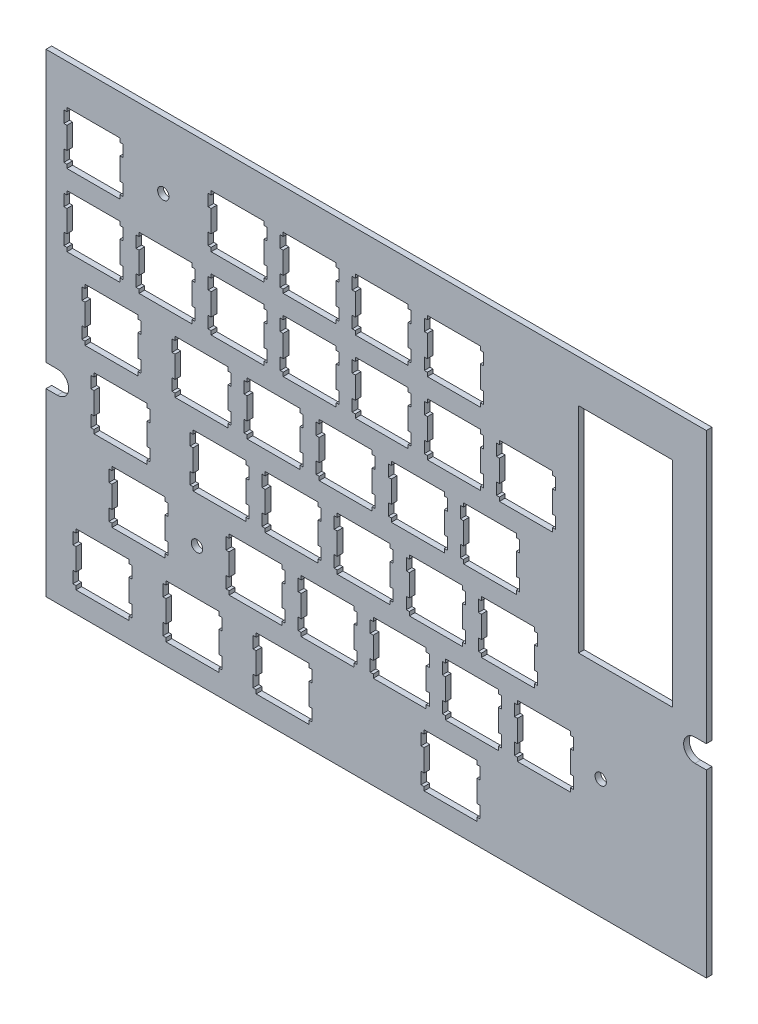
SolidWorks part; units mm, degrees
ref_plane "前视基准面" through (0, 0, 0) normal (0, 0, 1) x (1, 0, 0)
ref_plane "上视基准面" through (0, 0, 0) normal (0, 1, 0) x (1, 0, 0)
ref_plane "右视基准面" through (0, 0, 0) normal (1, 0, 0) x (0, 0, -1)
sketch "Model" plane through (0, 0, 0) normal (0, 0, 1) x (1, 0, 0)
  line L0 (392.6286, 110.8829) -> (392.6286, 109.8825)
  line L1 (392.6286, 109.8825) -> (391.8278, 109.8825)
  line L2 (391.8278, 109.8825) -> (391.8278, 106.7832)
  line L3 (391.8278, 106.7832) -> (392.6286, 106.7832)
  line L4 (392.6286, 106.7832) -> (392.6286, 100.9816)
  line L5 (392.6286, 100.9816) -> (391.8278, 100.9816)
  line L6 (391.8278, 100.9816) -> (391.8278, 97.8825)
  line L7 (391.8278, 97.8825) -> (392.6286, 97.8825)
  line L8 (392.6286, 97.8825) -> (392.6286, 96.882)
  line L9 (392.6286, 96.882) -> (406.6279, 96.882)
  line L10 (406.6279, 96.882) -> (406.6279, 97.8825)
  line L11 (406.6279, 97.8825) -> (407.4287, 97.8825)
  line L12 (407.4287, 97.8825) -> (407.4287, 100.9816)
  line L13 (407.4287, 100.9816) -> (406.6279, 100.9816)
  line L14 (406.6279, 100.9816) -> (406.6279, 106.7832)
  line L15 (406.6279, 106.7832) -> (407.4287, 106.7832)
  line L16 (407.4287, 106.7832) -> (407.4287, 109.8825)
  line L17 (407.4287, 109.8825) -> (406.6279, 109.8825)
  line L18 (406.6279, 109.8825) -> (406.6279, 110.8829)
  line L19 (406.6279, 110.8829) -> (392.6286, 110.8829)
  line L20 (368.8146, 110.8829) -> (368.8146, 109.8825)
  line L21 (368.8146, 109.8825) -> (368.0154, 109.8825)
  line L22 (368.0154, 109.8825) -> (368.0154, 106.7832)
  line L23 (368.0154, 106.7832) -> (368.8146, 106.7832)
  line L24 (368.8146, 106.7832) -> (368.8146, 100.9816)
  line L25 (368.8146, 100.9816) -> (368.0154, 100.9816)
  line L26 (368.0154, 100.9816) -> (368.0154, 97.8825)
  line L27 (368.0154, 97.8825) -> (368.8146, 97.8825)
  line L28 (368.8146, 97.8825) -> (368.8146, 96.882)
  line L29 (368.8146, 96.882) -> (382.8154, 96.882)
  line L30 (382.8154, 96.882) -> (382.8154, 97.8825)
  line L31 (382.8154, 97.8825) -> (383.6148, 97.8825)
  line L32 (383.6148, 97.8825) -> (383.6148, 100.9816)
  line L33 (383.6148, 100.9816) -> (382.8154, 100.9816)
  line L34 (382.8154, 100.9816) -> (382.8154, 106.7832)
  line L35 (382.8154, 106.7832) -> (383.6148, 106.7832)
  line L36 (383.6148, 106.7832) -> (383.6148, 109.8825)
  line L37 (383.6148, 109.8825) -> (382.8154, 109.8825)
  line L38 (382.8154, 109.8825) -> (382.8154, 110.8829)
  line L39 (382.8154, 110.8829) -> (368.8146, 110.8829)
  line L40 (345.0035, 110.8829) -> (345.0035, 109.8825)
  line L41 (345.0035, 109.8825) -> (344.2028, 109.8825)
  line L42 (344.2028, 109.8825) -> (344.2028, 106.7832)
  line L43 (344.2028, 106.7832) -> (345.0035, 106.7832)
  line L44 (345.0035, 106.7832) -> (345.0035, 100.9816)
  line L45 (345.0035, 100.9816) -> (344.2028, 100.9816)
  line L46 (344.2028, 100.9816) -> (344.2028, 97.8825)
  line L47 (344.2028, 97.8825) -> (345.0035, 97.8825)
  line L48 (345.0035, 97.8825) -> (345.0035, 96.882)
  line L49 (345.0035, 96.882) -> (359.003, 96.882)
  line L50 (359.003, 96.882) -> (359.003, 97.8825)
  line L51 (359.003, 97.8825) -> (359.8036, 97.8825)
  line L52 (359.8036, 97.8825) -> (359.8036, 100.9816)
  line L53 (359.8036, 100.9816) -> (359.003, 100.9816)
  line L54 (359.003, 100.9816) -> (359.003, 106.7832)
  line L55 (359.003, 106.7832) -> (359.8036, 106.7832)
  line L56 (359.8036, 106.7832) -> (359.8036, 109.8825)
  line L57 (359.8036, 109.8825) -> (359.003, 109.8825)
  line L58 (359.003, 109.8825) -> (359.003, 110.8829)
  line L59 (359.003, 110.8829) -> (345.0035, 110.8829)
  line L60 (461.6846, 129.9314) -> (461.6846, 128.9311)
  line L61 (461.6846, 128.9311) -> (460.8836, 128.9311)
  line L62 (460.8836, 128.9311) -> (460.8836, 125.8332)
  line L63 (460.8836, 125.8332) -> (461.6846, 125.8332)
  line L64 (461.6846, 125.8332) -> (461.6846, 120.0317)
  line L65 (461.6846, 120.0317) -> (460.8836, 120.0317)
  line L66 (460.8836, 120.0317) -> (460.8836, 116.9311)
  line L67 (460.8836, 116.9311) -> (461.6846, 116.9311)
  line L68 (461.6846, 116.9311) -> (461.6846, 115.932)
  line L69 (461.6846, 115.932) -> (475.6846, 115.932)
  line L70 (475.6846, 115.932) -> (475.6846, 116.9311)
  line L71 (475.6846, 116.9311) -> (476.4836, 116.9311)
  line L72 (476.4836, 116.9311) -> (476.4836, 120.0317)
  line L73 (476.4836, 120.0317) -> (475.6846, 120.0317)
  line L74 (475.6846, 120.0317) -> (475.6846, 125.8332)
  line L75 (475.6846, 125.8332) -> (476.4836, 125.8332)
  line L76 (476.4836, 125.8332) -> (476.4836, 128.9311)
  line L77 (476.4836, 128.9311) -> (475.6846, 128.9311)
  line L78 (475.6846, 128.9311) -> (475.6846, 129.9314)
  line L79 (475.6846, 129.9314) -> (461.6846, 129.9314)
  line L80 (442.6346, 129.9314) -> (442.6346, 128.9311)
  line L81 (442.6346, 128.9311) -> (441.8336, 128.9311)
  line L82 (441.8336, 128.9311) -> (441.8336, 125.8332)
  line L83 (441.8336, 125.8332) -> (442.6346, 125.8332)
  line L84 (442.6346, 125.8332) -> (442.6346, 120.0317)
  line L85 (442.6346, 120.0317) -> (441.8336, 120.0317)
  line L86 (441.8336, 120.0317) -> (441.8336, 116.9311)
  line L87 (441.8336, 116.9311) -> (442.6346, 116.9311)
  line L88 (442.6346, 116.9311) -> (442.6346, 115.932)
  line L89 (442.6346, 115.932) -> (456.6346, 115.932)
  line L90 (456.6346, 115.932) -> (456.6346, 116.9311)
  line L91 (456.6346, 116.9311) -> (457.4336, 116.9311)
  line L92 (457.4336, 116.9311) -> (457.4336, 120.0317)
  line L93 (457.4336, 120.0317) -> (456.6346, 120.0317)
  line L94 (456.6346, 120.0317) -> (456.6346, 125.8332)
  line L95 (456.6346, 125.8332) -> (457.4336, 125.8332)
  line L96 (457.4336, 125.8332) -> (457.4336, 128.9311)
  line L97 (457.4336, 128.9311) -> (456.6346, 128.9311)
  line L98 (456.6346, 128.9311) -> (456.6346, 129.9314)
  line L99 (456.6346, 129.9314) -> (442.6346, 129.9314)
  line L100 (423.5848, 129.9314) -> (423.5848, 128.9311)
  line L101 (423.5848, 128.9311) -> (422.784, 128.9311)
  line L102 (422.784, 128.9311) -> (422.784, 125.8332)
  line L103 (422.784, 125.8332) -> (423.5848, 125.8332)
  line L104 (423.5848, 125.8332) -> (423.5848, 120.0317)
  line L105 (423.5848, 120.0317) -> (422.784, 120.0317)
  line L106 (422.784, 120.0317) -> (422.784, 116.9311)
  line L107 (422.784, 116.9311) -> (423.5848, 116.9311)
  line L108 (423.5848, 116.9311) -> (423.5848, 115.932)
  line L109 (423.5848, 115.932) -> (437.5841, 115.932)
  line L110 (437.5841, 115.932) -> (437.5841, 116.9311)
  line L111 (437.5841, 116.9311) -> (438.3835, 116.9311)
  line L112 (438.3835, 116.9311) -> (438.3835, 120.0317)
  line L113 (438.3835, 120.0317) -> (437.5841, 120.0317)
  line L114 (437.5841, 120.0317) -> (437.5841, 125.8332)
  line L115 (437.5841, 125.8332) -> (438.3835, 125.8332)
  line L116 (438.3835, 125.8332) -> (438.3835, 128.9311)
  line L117 (438.3835, 128.9311) -> (437.5841, 128.9311)
  line L118 (437.5841, 128.9311) -> (437.5841, 129.9314)
  line L119 (437.5841, 129.9314) -> (423.5848, 129.9314)
  line L120 (404.5348, 129.9314) -> (404.5348, 128.9311)
  line L121 (404.5348, 128.9311) -> (403.734, 128.9311)
  line L122 (403.734, 128.9311) -> (403.734, 125.8332)
  line L123 (403.734, 125.8332) -> (404.5348, 125.8332)
  line L124 (404.5348, 125.8332) -> (404.5348, 120.0317)
  line L125 (404.5348, 120.0317) -> (403.734, 120.0317)
  line L126 (403.734, 120.0317) -> (403.734, 116.9311)
  line L127 (403.734, 116.9311) -> (404.5348, 116.9311)
  line L128 (404.5348, 116.9311) -> (404.5348, 115.932)
  line L129 (404.5348, 115.932) -> (418.5341, 115.932)
  line L130 (418.5341, 115.932) -> (418.5341, 116.9311)
  line L131 (418.5341, 116.9311) -> (419.3335, 116.9311)
  line L132 (419.3335, 116.9311) -> (419.3335, 120.0317)
  line L133 (419.3335, 120.0317) -> (418.5341, 120.0317)
  line L134 (418.5341, 120.0317) -> (418.5341, 125.8332)
  line L135 (418.5341, 125.8332) -> (419.3335, 125.8332)
  line L136 (419.3335, 125.8332) -> (419.3335, 128.9311)
  line L137 (419.3335, 128.9311) -> (418.5341, 128.9311)
  line L138 (418.5341, 128.9311) -> (418.5341, 129.9314)
  line L139 (418.5341, 129.9314) -> (404.5348, 129.9314)
  line L140 (385.4848, 129.9314) -> (385.4848, 128.9311)
  line L141 (385.4848, 128.9311) -> (384.684, 128.9311)
  line L142 (384.684, 128.9311) -> (384.684, 125.8332)
  line L143 (384.684, 125.8332) -> (385.4848, 125.8332)
  line L144 (385.4848, 125.8332) -> (385.4848, 120.0317)
  line L145 (385.4848, 120.0317) -> (384.684, 120.0317)
  line L146 (384.684, 120.0317) -> (384.684, 116.9311)
  line L147 (384.684, 116.9311) -> (385.4848, 116.9311)
  line L148 (385.4848, 116.9311) -> (385.4848, 115.932)
  line L149 (385.4848, 115.932) -> (399.4841, 115.932)
  line L150 (399.4841, 115.932) -> (399.4841, 116.9311)
  line L151 (399.4841, 116.9311) -> (400.2835, 116.9311)
  line L152 (400.2835, 116.9311) -> (400.2835, 120.0317)
  line L153 (400.2835, 120.0317) -> (399.4841, 120.0317)
  line L154 (399.4841, 120.0317) -> (399.4841, 125.8332)
  line L155 (399.4841, 125.8332) -> (400.2835, 125.8332)
  line L156 (400.2835, 125.8332) -> (400.2835, 128.9311)
  line L157 (400.2835, 128.9311) -> (399.4841, 128.9311)
  line L158 (399.4841, 128.9311) -> (399.4841, 129.9314)
  line L159 (399.4841, 129.9314) -> (385.4848, 129.9314)
  line L160 (452.1596, 148.9815) -> (452.1596, 147.981)
  line L161 (452.1596, 147.981) -> (451.3586, 147.981)
  line L162 (451.3586, 147.981) -> (451.3586, 144.8832)
  line L163 (451.3586, 144.8832) -> (452.1596, 144.8832)
  line L164 (452.1596, 144.8832) -> (452.1596, 139.0818)
  line L165 (452.1596, 139.0818) -> (451.3586, 139.0818)
  line L166 (451.3586, 139.0818) -> (451.3586, 135.9812)
  line L167 (451.3586, 135.9812) -> (452.1596, 135.9812)
  line L168 (452.1596, 135.9812) -> (452.1596, 134.9822)
  line L169 (452.1596, 134.9822) -> (466.1596, 134.9822)
  line L170 (466.1596, 134.9822) -> (466.1596, 135.9812)
  line L171 (466.1596, 135.9812) -> (466.9586, 135.9812)
  line L172 (466.9586, 135.9812) -> (466.9586, 139.0818)
  line L173 (466.9586, 139.0818) -> (466.1596, 139.0818)
  line L174 (466.1596, 139.0818) -> (466.1596, 144.8832)
  line L175 (466.1596, 144.8832) -> (466.9586, 144.8832)
  line L176 (466.9586, 144.8832) -> (466.9586, 147.981)
  line L177 (466.9586, 147.981) -> (466.1596, 147.981)
  line L178 (466.1596, 147.981) -> (466.1596, 148.9815)
  line L179 (466.1596, 148.9815) -> (452.1596, 148.9815)
  line L180 (433.1098, 148.9815) -> (433.1098, 147.981)
  line L181 (433.1098, 147.981) -> (432.309, 147.981)
  line L182 (432.309, 147.981) -> (432.309, 144.8832)
  line L183 (432.309, 144.8832) -> (433.1098, 144.8832)
  line L184 (433.1098, 144.8832) -> (433.1098, 139.0818)
  line L185 (433.1098, 139.0818) -> (432.309, 139.0818)
  line L186 (432.309, 139.0818) -> (432.309, 135.9812)
  line L187 (432.309, 135.9812) -> (433.1098, 135.9812)
  line L188 (433.1098, 135.9812) -> (433.1098, 134.9822)
  line L189 (433.1098, 134.9822) -> (447.1096, 134.9822)
  line L190 (447.1096, 134.9822) -> (447.1096, 135.9812)
  line L191 (447.1096, 135.9812) -> (447.9086, 135.9812)
  line L192 (447.9086, 135.9812) -> (447.9086, 139.0818)
  line L193 (447.9086, 139.0818) -> (447.1096, 139.0818)
  line L194 (447.1096, 139.0818) -> (447.1096, 144.8832)
  line L195 (447.1096, 144.8832) -> (447.9086, 144.8832)
  line L196 (447.9086, 144.8832) -> (447.9086, 147.981)
  line L197 (447.9086, 147.981) -> (447.1096, 147.981)
  line L198 (447.1096, 147.981) -> (447.1096, 148.9815)
  line L199 (447.1096, 148.9815) -> (433.1098, 148.9815)
  line L200 (414.0598, 148.9815) -> (414.0598, 147.981)
  line L201 (414.0598, 147.981) -> (413.259, 147.981)
  line L202 (413.259, 147.981) -> (413.259, 144.8832)
  line L203 (413.259, 144.8832) -> (414.0598, 144.8832)
  line L204 (414.0598, 144.8832) -> (414.0598, 139.0818)
  line L205 (414.0598, 139.0818) -> (413.259, 139.0818)
  line L206 (413.259, 139.0818) -> (413.259, 135.9812)
  line L207 (413.259, 135.9812) -> (414.0598, 135.9812)
  line L208 (414.0598, 135.9812) -> (414.0598, 134.9822)
  line L209 (414.0598, 134.9822) -> (428.0591, 134.9822)
  line L210 (428.0591, 134.9822) -> (428.0591, 135.9812)
  line L211 (428.0591, 135.9812) -> (428.8585, 135.9812)
  line L212 (428.8585, 135.9812) -> (428.8585, 139.0818)
  line L213 (428.8585, 139.0818) -> (428.0591, 139.0818)
  line L214 (428.0591, 139.0818) -> (428.0591, 144.8832)
  line L215 (428.0591, 144.8832) -> (428.8585, 144.8832)
  line L216 (428.8585, 144.8832) -> (428.8585, 147.981)
  line L217 (428.8585, 147.981) -> (428.0591, 147.981)
  line L218 (428.0591, 147.981) -> (428.0591, 148.9815)
  line L219 (428.0591, 148.9815) -> (414.0598, 148.9815)
  line L220 (395.0098, 148.9815) -> (395.0098, 147.981)
  line L221 (395.0098, 147.981) -> (394.209, 147.981)
  line L222 (394.209, 147.981) -> (394.209, 144.8832)
  line L223 (394.209, 144.8832) -> (395.0098, 144.8832)
  line L224 (395.0098, 144.8832) -> (395.0098, 139.0818)
  line L225 (395.0098, 139.0818) -> (394.209, 139.0818)
  line L226 (394.209, 139.0818) -> (394.209, 135.9812)
  line L227 (394.209, 135.9812) -> (395.0098, 135.9812)
  line L228 (395.0098, 135.9812) -> (395.0098, 134.9822)
  line L229 (395.0098, 134.9822) -> (409.0091, 134.9822)
  line L230 (409.0091, 134.9822) -> (409.0091, 135.9812)
  line L231 (409.0091, 135.9812) -> (409.8085, 135.9812)
  line L232 (409.8085, 135.9812) -> (409.8085, 139.0818)
  line L233 (409.8085, 139.0818) -> (409.0091, 139.0818)
  line L234 (409.0091, 139.0818) -> (409.0091, 144.8832)
  line L235 (409.0091, 144.8832) -> (409.8085, 144.8832)
  line L236 (409.8085, 144.8832) -> (409.8085, 147.981)
  line L237 (409.8085, 147.981) -> (409.0091, 147.981)
  line L238 (409.0091, 147.981) -> (409.0091, 148.9815)
  line L239 (409.0091, 148.9815) -> (395.0098, 148.9815)
  line L240 (375.9598, 148.9815) -> (375.9598, 147.981)
  line L241 (375.9598, 147.981) -> (375.1591, 147.981)
  line L242 (375.1591, 147.981) -> (375.1591, 144.8832)
  line L243 (375.1591, 144.8832) -> (375.9598, 144.8832)
  line L244 (375.9598, 144.8832) -> (375.9598, 139.0818)
  line L245 (375.9598, 139.0818) -> (375.1591, 139.0818)
  line L246 (375.1591, 139.0818) -> (375.1591, 135.9812)
  line L247 (375.1591, 135.9812) -> (375.9598, 135.9812)
  line L248 (375.9598, 135.9812) -> (375.9598, 134.9822)
  line L249 (375.9598, 134.9822) -> (389.9591, 134.9822)
  line L250 (389.9591, 134.9822) -> (389.9591, 135.9812)
  line L251 (389.9591, 135.9812) -> (390.7585, 135.9812)
  line L252 (390.7585, 135.9812) -> (390.7585, 139.0818)
  line L253 (390.7585, 139.0818) -> (389.9591, 139.0818)
  line L254 (389.9591, 139.0818) -> (389.9591, 144.8832)
  line L255 (389.9591, 144.8832) -> (390.7585, 144.8832)
  line L256 (390.7585, 144.8832) -> (390.7585, 147.981)
  line L257 (390.7585, 147.981) -> (389.9591, 147.981)
  line L258 (389.9591, 147.981) -> (389.9591, 148.9815)
  line L259 (389.9591, 148.9815) -> (375.9598, 148.9815)
  line L260 (349.7646, 148.9815) -> (349.7646, 147.981)
  line L261 (349.7646, 147.981) -> (348.9653, 147.981)
  line L262 (348.9653, 147.981) -> (348.9653, 144.8832)
  line L263 (348.9653, 144.8832) -> (349.7646, 144.8832)
  line L264 (349.7646, 144.8832) -> (349.7646, 139.0818)
  line L265 (349.7646, 139.0818) -> (348.9653, 139.0818)
  line L266 (348.9653, 139.0818) -> (348.9653, 135.9812)
  line L267 (348.9653, 135.9812) -> (349.7646, 135.9812)
  line L268 (349.7646, 135.9812) -> (349.7646, 134.9822)
  line L269 (349.7646, 134.9822) -> (363.7655, 134.9822)
  line L270 (363.7655, 134.9822) -> (363.7655, 135.9812)
  line L271 (363.7655, 135.9812) -> (364.5648, 135.9812)
  line L272 (364.5648, 135.9812) -> (364.5648, 139.0818)
  line L273 (364.5648, 139.0818) -> (363.7655, 139.0818)
  line L274 (363.7655, 139.0818) -> (363.7655, 144.8832)
  line L275 (363.7655, 144.8832) -> (364.5648, 144.8832)
  line L276 (364.5648, 144.8832) -> (364.5648, 147.981)
  line L277 (364.5648, 147.981) -> (363.7655, 147.981)
  line L278 (363.7655, 147.981) -> (363.7655, 148.9815)
  line L279 (363.7655, 148.9815) -> (349.7646, 148.9815)
  line L280 (447.3976, 168.0315) -> (447.3976, 167.031)
  line L281 (447.3976, 167.031) -> (446.5966, 167.031)
  line L282 (446.5966, 167.031) -> (446.5966, 163.9318)
  line L283 (446.5966, 163.9318) -> (447.3976, 163.9318)
  line L284 (447.3976, 163.9318) -> (447.3976, 158.1318)
  line L285 (447.3976, 158.1318) -> (446.5966, 158.1318)
  line L286 (446.5966, 158.1318) -> (446.5966, 155.0312)
  line L287 (446.5966, 155.0312) -> (447.3976, 155.0312)
  line L288 (447.3976, 155.0312) -> (447.3976, 154.0322)
  line L289 (447.3976, 154.0322) -> (461.3966, 154.0322)
  line L290 (461.3966, 154.0322) -> (461.3966, 155.0312)
  line L291 (461.3966, 155.0312) -> (462.1976, 155.0312)
  line L292 (462.1976, 155.0312) -> (462.1976, 158.1318)
  line L293 (462.1976, 158.1318) -> (461.3966, 158.1318)
  line L294 (461.3966, 158.1318) -> (461.3966, 163.9318)
  line L295 (461.3966, 163.9318) -> (462.1976, 163.9318)
  line L296 (462.1976, 163.9318) -> (462.1976, 167.031)
  line L297 (462.1976, 167.031) -> (461.3966, 167.031)
  line L298 (461.3966, 167.031) -> (461.3966, 168.0315)
  line L299 (461.3966, 168.0315) -> (447.3976, 168.0315)
  line L300 (428.3473, 168.0315) -> (428.3473, 167.031)
  line L301 (428.3473, 167.031) -> (427.5465, 167.031)
  line L302 (427.5465, 167.031) -> (427.5465, 163.9318)
  line L303 (427.5465, 163.9318) -> (428.3473, 163.9318)
  line L304 (428.3473, 163.9318) -> (428.3473, 158.1318)
  line L305 (428.3473, 158.1318) -> (427.5465, 158.1318)
  line L306 (427.5465, 158.1318) -> (427.5465, 155.0312)
  line L307 (427.5465, 155.0312) -> (428.3473, 155.0312)
  line L308 (428.3473, 155.0312) -> (428.3473, 154.0322)
  line L309 (428.3473, 154.0322) -> (442.3466, 154.0322)
  line L310 (442.3466, 154.0322) -> (442.3466, 155.0312)
  line L311 (442.3466, 155.0312) -> (443.1476, 155.0312)
  line L312 (443.1476, 155.0312) -> (443.1476, 158.1318)
  line L313 (443.1476, 158.1318) -> (442.3466, 158.1318)
  line L314 (442.3466, 158.1318) -> (442.3466, 163.9318)
  line L315 (442.3466, 163.9318) -> (443.1476, 163.9318)
  line L316 (443.1476, 163.9318) -> (443.1476, 167.031)
  line L317 (443.1476, 167.031) -> (442.3466, 167.031)
  line L318 (442.3466, 167.031) -> (442.3466, 168.0315)
  line L319 (442.3466, 168.0315) -> (428.3473, 168.0315)
  line L320 (409.2973, 168.0315) -> (409.2973, 167.031)
  line L321 (409.2973, 167.031) -> (408.4965, 167.031)
  line L322 (408.4965, 167.031) -> (408.4965, 163.9318)
  line L323 (408.4965, 163.9318) -> (409.2973, 163.9318)
  line L324 (409.2973, 163.9318) -> (409.2973, 158.1318)
  line L325 (409.2973, 158.1318) -> (408.4965, 158.1318)
  line L326 (408.4965, 158.1318) -> (408.4965, 155.0312)
  line L327 (408.4965, 155.0312) -> (409.2973, 155.0312)
  line L328 (409.2973, 155.0312) -> (409.2973, 154.0322)
  line L329 (409.2973, 154.0322) -> (423.2966, 154.0322)
  line L330 (423.2966, 154.0322) -> (423.2966, 155.0312)
  line L331 (423.2966, 155.0312) -> (424.0974, 155.0312)
  line L332 (424.0974, 155.0312) -> (424.0974, 158.1318)
  line L333 (424.0974, 158.1318) -> (423.2966, 158.1318)
  line L334 (423.2966, 158.1318) -> (423.2966, 163.9318)
  line L335 (423.2966, 163.9318) -> (424.0974, 163.9318)
  line L336 (424.0974, 163.9318) -> (424.0974, 167.031)
  line L337 (424.0974, 167.031) -> (423.2966, 167.031)
  line L338 (423.2966, 167.031) -> (423.2966, 168.0315)
  line L339 (423.2966, 168.0315) -> (409.2973, 168.0315)
  line L340 (390.2473, 168.0315) -> (390.2473, 167.031)
  line L341 (390.2473, 167.031) -> (389.4465, 167.031)
  line L342 (389.4465, 167.031) -> (389.4465, 163.9318)
  line L343 (389.4465, 163.9318) -> (390.2473, 163.9318)
  line L344 (390.2473, 163.9318) -> (390.2473, 158.1318)
  line L345 (390.2473, 158.1318) -> (389.4465, 158.1318)
  line L346 (389.4465, 158.1318) -> (389.4465, 155.0312)
  line L347 (389.4465, 155.0312) -> (390.2473, 155.0312)
  line L348 (390.2473, 155.0312) -> (390.2473, 154.0322)
  line L349 (390.2473, 154.0322) -> (404.2466, 154.0322)
  line L350 (404.2466, 154.0322) -> (404.2466, 155.0312)
  line L351 (404.2466, 155.0312) -> (405.0474, 155.0312)
  line L352 (405.0474, 155.0312) -> (405.0474, 158.1318)
  line L353 (405.0474, 158.1318) -> (404.2466, 158.1318)
  line L354 (404.2466, 158.1318) -> (404.2466, 163.9318)
  line L355 (404.2466, 163.9318) -> (405.0474, 163.9318)
  line L356 (405.0474, 163.9318) -> (405.0474, 167.031)
  line L357 (405.0474, 167.031) -> (404.2466, 167.031)
  line L358 (404.2466, 167.031) -> (404.2466, 168.0315)
  line L359 (404.2466, 168.0315) -> (390.2473, 168.0315)
  line L360 (371.1973, 168.0315) -> (371.1973, 167.031)
  line L361 (371.1973, 167.031) -> (370.3966, 167.031)
  line L362 (370.3966, 167.031) -> (370.3966, 163.9318)
  line L363 (370.3966, 163.9318) -> (371.1973, 163.9318)
  line L364 (371.1973, 163.9318) -> (371.1973, 158.1318)
  line L365 (371.1973, 158.1318) -> (370.3966, 158.1318)
  line L366 (370.3966, 158.1318) -> (370.3966, 155.0312)
  line L367 (370.3966, 155.0312) -> (371.1973, 155.0312)
  line L368 (371.1973, 155.0312) -> (371.1973, 154.0322)
  line L369 (371.1973, 154.0322) -> (385.1966, 154.0322)
  line L370 (385.1966, 154.0322) -> (385.1966, 155.0312)
  line L371 (385.1966, 155.0312) -> (385.9974, 155.0312)
  line L372 (385.9974, 155.0312) -> (385.9974, 158.1318)
  line L373 (385.9974, 158.1318) -> (385.1966, 158.1318)
  line L374 (385.1966, 158.1318) -> (385.1966, 163.9318)
  line L375 (385.1966, 163.9318) -> (385.9974, 163.9318)
  line L376 (385.9974, 163.9318) -> (385.9974, 167.031)
  line L377 (385.9974, 167.031) -> (385.1966, 167.031)
  line L378 (385.1966, 167.031) -> (385.1966, 168.0315)
  line L379 (385.1966, 168.0315) -> (371.1973, 168.0315)
  line L380 (347.3847, 168.0315) -> (347.3847, 167.031)
  line L381 (347.3847, 167.031) -> (346.5841, 167.031)
  line L382 (346.5841, 167.031) -> (346.5841, 163.9318)
  line L383 (346.5841, 163.9318) -> (347.3847, 163.9318)
  line L384 (347.3847, 163.9318) -> (347.3847, 158.1318)
  line L385 (347.3847, 158.1318) -> (346.5841, 158.1318)
  line L386 (346.5841, 158.1318) -> (346.5841, 155.0312)
  line L387 (346.5841, 155.0312) -> (347.3847, 155.0312)
  line L388 (347.3847, 155.0312) -> (347.3847, 154.0322)
  line L389 (347.3847, 154.0322) -> (361.3843, 154.0322)
  line L390 (361.3843, 154.0322) -> (361.3843, 155.0312)
  line L391 (361.3843, 155.0312) -> (362.1835, 155.0312)
  line L392 (362.1835, 155.0312) -> (362.1835, 158.1318)
  line L393 (362.1835, 158.1318) -> (361.3843, 158.1318)
  line L394 (361.3843, 158.1318) -> (361.3843, 163.9318)
  line L395 (361.3843, 163.9318) -> (362.1835, 163.9318)
  line L396 (362.1835, 163.9318) -> (362.1835, 167.031)
  line L397 (362.1835, 167.031) -> (361.3843, 167.031)
  line L398 (361.3843, 167.031) -> (361.3843, 168.0315)
  line L399 (361.3843, 168.0315) -> (347.3847, 168.0315)
  line L400 (456.9206, 187.0815) -> (456.9206, 186.081)
  line L401 (456.9206, 186.081) -> (456.1216, 186.081)
  line L402 (456.1216, 186.081) -> (456.1216, 182.9818)
  line L403 (456.1216, 182.9818) -> (456.9206, 182.9818)
  line L404 (456.9206, 182.9818) -> (456.9206, 177.1818)
  line L405 (456.9206, 177.1818) -> (456.1216, 177.1818)
  line L406 (456.1216, 177.1818) -> (456.1216, 174.0812)
  line L407 (456.1216, 174.0812) -> (456.9206, 174.0812)
  line L408 (456.9206, 174.0812) -> (456.9206, 173.0822)
  line L409 (456.9206, 173.0822) -> (470.9216, 173.0822)
  line L410 (470.9216, 173.0822) -> (470.9216, 174.0812)
  line L411 (470.9216, 174.0812) -> (471.7226, 174.0812)
  line L412 (471.7226, 174.0812) -> (471.7226, 177.1818)
  line L413 (471.7226, 177.1818) -> (470.9216, 177.1818)
  line L414 (470.9216, 177.1818) -> (470.9216, 182.9818)
  line L415 (470.9216, 182.9818) -> (471.7226, 182.9818)
  line L416 (471.7226, 182.9818) -> (471.7226, 186.081)
  line L417 (471.7226, 186.081) -> (470.9216, 186.081)
  line L418 (470.9216, 186.081) -> (470.9216, 187.0815)
  line L419 (470.9216, 187.0815) -> (456.9206, 187.0815)
  line L420 (437.8709, 187.0815) -> (437.8709, 186.081)
  line L421 (437.8709, 186.081) -> (437.0715, 186.081)
  line L422 (437.0715, 186.081) -> (437.0715, 182.9818)
  line L423 (437.0715, 182.9818) -> (437.8709, 182.9818)
  line L424 (437.8709, 182.9818) -> (437.8709, 177.1818)
  line L425 (437.8709, 177.1818) -> (437.0715, 177.1818)
  line L426 (437.0715, 177.1818) -> (437.0715, 174.0812)
  line L427 (437.0715, 174.0812) -> (437.8709, 174.0812)
  line L428 (437.8709, 174.0812) -> (437.8709, 173.0822)
  line L429 (437.8709, 173.0822) -> (451.8716, 173.0822)
  line L430 (451.8716, 173.0822) -> (451.8716, 174.0812)
  line L431 (451.8716, 174.0812) -> (452.6706, 174.0812)
  line L432 (452.6706, 174.0812) -> (452.6706, 177.1818)
  line L433 (452.6706, 177.1818) -> (451.8716, 177.1818)
  line L434 (451.8716, 177.1818) -> (451.8716, 182.9818)
  line L435 (451.8716, 182.9818) -> (452.6706, 182.9818)
  line L436 (452.6706, 182.9818) -> (452.6706, 186.081)
  line L437 (452.6706, 186.081) -> (451.8716, 186.081)
  line L438 (451.8716, 186.081) -> (451.8716, 187.0815)
  line L439 (451.8716, 187.0815) -> (437.8709, 187.0815)
  line L440 (418.8223, 187.0815) -> (418.8223, 186.081)
  line L441 (418.8223, 186.081) -> (418.0215, 186.081)
  line L442 (418.0215, 186.081) -> (418.0215, 182.9818)
  line L443 (418.0215, 182.9818) -> (418.8223, 182.9818)
  line L444 (418.8223, 182.9818) -> (418.8223, 177.1818)
  line L445 (418.8223, 177.1818) -> (418.0215, 177.1818)
  line L446 (418.0215, 177.1818) -> (418.0215, 174.0812)
  line L447 (418.0215, 174.0812) -> (418.8223, 174.0812)
  line L448 (418.8223, 174.0812) -> (418.8223, 173.0822)
  line L449 (418.8223, 173.0822) -> (432.8216, 173.0822)
  line L450 (432.8216, 173.0822) -> (432.8216, 174.0812)
  line L451 (432.8216, 174.0812) -> (433.621, 174.0812)
  line L452 (433.621, 174.0812) -> (433.621, 177.1818)
  line L453 (433.621, 177.1818) -> (432.8216, 177.1818)
  line L454 (432.8216, 177.1818) -> (432.8216, 182.9818)
  line L455 (432.8216, 182.9818) -> (433.621, 182.9818)
  line L456 (433.621, 182.9818) -> (433.621, 186.081)
  line L457 (433.621, 186.081) -> (432.8216, 186.081)
  line L458 (432.8216, 186.081) -> (432.8216, 187.0815)
  line L459 (432.8216, 187.0815) -> (418.8223, 187.0815)
  line L460 (399.7723, 187.0815) -> (399.7723, 186.081)
  line L461 (399.7723, 186.081) -> (398.9715, 186.081)
  line L462 (398.9715, 186.081) -> (398.9715, 182.9818)
  line L463 (398.9715, 182.9818) -> (399.7723, 182.9818)
  line L464 (399.7723, 182.9818) -> (399.7723, 177.1818)
  line L465 (399.7723, 177.1818) -> (398.9715, 177.1818)
  line L466 (398.9715, 177.1818) -> (398.9715, 174.0812)
  line L467 (398.9715, 174.0812) -> (399.7723, 174.0812)
  line L468 (399.7723, 174.0812) -> (399.7723, 173.0822)
  line L469 (399.7723, 173.0822) -> (413.7716, 173.0822)
  line L470 (413.7716, 173.0822) -> (413.7716, 174.0812)
  line L471 (413.7716, 174.0812) -> (414.5724, 174.0812)
  line L472 (414.5724, 174.0812) -> (414.5724, 177.1818)
  line L473 (414.5724, 177.1818) -> (413.7716, 177.1818)
  line L474 (413.7716, 177.1818) -> (413.7716, 182.9818)
  line L475 (413.7716, 182.9818) -> (414.5724, 182.9818)
  line L476 (414.5724, 182.9818) -> (414.5724, 186.081)
  line L477 (414.5724, 186.081) -> (413.7716, 186.081)
  line L478 (413.7716, 186.081) -> (413.7716, 187.0815)
  line L479 (413.7716, 187.0815) -> (399.7723, 187.0815)
  line L480 (380.7223, 187.0815) -> (380.7223, 186.081)
  line L481 (380.7223, 186.081) -> (379.9215, 186.081)
  line L482 (379.9215, 186.081) -> (379.9215, 182.9818)
  line L483 (379.9215, 182.9818) -> (380.7223, 182.9818)
  line L484 (380.7223, 182.9818) -> (380.7223, 177.1818)
  line L485 (380.7223, 177.1818) -> (379.9215, 177.1818)
  line L486 (379.9215, 177.1818) -> (379.9215, 174.0812)
  line L487 (379.9215, 174.0812) -> (380.7223, 174.0812)
  line L488 (380.7223, 174.0812) -> (380.7223, 173.0822)
  line L489 (380.7223, 173.0822) -> (394.7216, 173.0822)
  line L490 (394.7216, 173.0822) -> (394.7216, 174.0812)
  line L491 (394.7216, 174.0812) -> (395.5224, 174.0812)
  line L492 (395.5224, 174.0812) -> (395.5224, 177.1818)
  line L493 (395.5224, 177.1818) -> (394.7216, 177.1818)
  line L494 (394.7216, 177.1818) -> (394.7216, 182.9818)
  line L495 (394.7216, 182.9818) -> (395.5224, 182.9818)
  line L496 (395.5224, 182.9818) -> (395.5224, 186.081)
  line L497 (395.5224, 186.081) -> (394.7216, 186.081)
  line L498 (394.7216, 186.081) -> (394.7216, 187.0815)
  line L499 (394.7216, 187.0815) -> (380.7223, 187.0815)
  line L500 (361.6723, 187.0815) -> (361.6723, 186.081)
  line L501 (361.6723, 186.081) -> (360.8716, 186.081)
  line L502 (360.8716, 186.081) -> (360.8716, 182.9818)
  line L503 (360.8716, 182.9818) -> (361.6723, 182.9818)
  line L504 (361.6723, 182.9818) -> (361.6723, 177.1818)
  line L505 (361.6723, 177.1818) -> (360.8716, 177.1818)
  line L506 (360.8716, 177.1818) -> (360.8716, 174.0812)
  line L507 (360.8716, 174.0812) -> (361.6723, 174.0812)
  line L508 (361.6723, 174.0812) -> (361.6723, 173.0822)
  line L509 (361.6723, 173.0822) -> (375.6716, 173.0822)
  line L510 (375.6716, 173.0822) -> (375.6716, 174.0812)
  line L511 (375.6716, 174.0812) -> (376.4724, 174.0812)
  line L512 (376.4724, 174.0812) -> (376.4724, 177.1818)
  line L513 (376.4724, 177.1818) -> (375.6716, 177.1818)
  line L514 (375.6716, 177.1818) -> (375.6716, 182.9818)
  line L515 (375.6716, 182.9818) -> (376.4724, 182.9818)
  line L516 (376.4724, 182.9818) -> (376.4724, 186.081)
  line L517 (376.4724, 186.081) -> (375.6716, 186.081)
  line L518 (375.6716, 186.081) -> (375.6716, 187.0815)
  line L519 (375.6716, 187.0815) -> (361.6723, 187.0815)
  line L520 (342.6222, 187.0815) -> (342.6222, 186.081)
  line L521 (342.6222, 186.081) -> (341.8216, 186.081)
  line L522 (341.8216, 186.081) -> (341.8216, 182.9818)
  line L523 (341.8216, 182.9818) -> (342.6222, 182.9818)
  line L524 (342.6222, 182.9818) -> (342.6222, 177.1818)
  line L525 (342.6222, 177.1818) -> (341.8216, 177.1818)
  line L526 (341.8216, 177.1818) -> (341.8216, 174.0812)
  line L527 (341.8216, 174.0812) -> (342.6222, 174.0812)
  line L528 (342.6222, 174.0812) -> (342.6222, 173.0822)
  line L529 (342.6222, 173.0822) -> (356.6218, 173.0822)
  line L530 (356.6218, 173.0822) -> (356.6218, 174.0812)
  line L531 (356.6218, 174.0812) -> (357.4224, 174.0812)
  line L532 (357.4224, 174.0812) -> (357.4224, 177.1818)
  line L533 (357.4224, 177.1818) -> (356.6218, 177.1818)
  line L534 (356.6218, 177.1818) -> (356.6218, 182.9818)
  line L535 (356.6218, 182.9818) -> (357.4224, 182.9818)
  line L536 (357.4224, 182.9818) -> (357.4224, 186.081)
  line L537 (357.4224, 186.081) -> (356.6218, 186.081)
  line L538 (356.6218, 186.081) -> (356.6218, 187.0815)
  line L539 (356.6218, 187.0815) -> (342.6222, 187.0815)
  line L540 (437.8709, 206.1314) -> (437.8709, 205.1314)
  line L541 (437.8709, 205.1314) -> (437.0715, 205.1314)
  line L542 (437.0715, 205.1314) -> (437.0715, 202.0314)
  line L543 (437.0715, 202.0314) -> (437.8709, 202.0314)
  line L544 (437.8709, 202.0314) -> (437.8709, 196.2314)
  line L545 (437.8709, 196.2314) -> (437.0715, 196.2314)
  line L546 (437.0715, 196.2314) -> (437.0715, 193.1312)
  line L547 (437.0715, 193.1312) -> (437.8709, 193.1312)
  line L548 (437.8709, 193.1312) -> (437.8709, 192.1322)
  line L549 (437.8709, 192.1322) -> (451.8716, 192.1322)
  line L550 (451.8716, 192.1322) -> (451.8716, 193.1312)
  line L551 (451.8716, 193.1312) -> (452.6706, 193.1312)
  line L552 (452.6706, 193.1312) -> (452.6706, 196.2314)
  line L553 (452.6706, 196.2314) -> (451.8716, 196.2314)
  line L554 (451.8716, 196.2314) -> (451.8716, 202.0314)
  line L555 (451.8716, 202.0314) -> (452.6706, 202.0314)
  line L556 (452.6706, 202.0314) -> (452.6706, 205.1314)
  line L557 (452.6706, 205.1314) -> (451.8716, 205.1314)
  line L558 (451.8716, 205.1314) -> (451.8716, 206.1314)
  line L559 (451.8716, 206.1314) -> (437.8709, 206.1314)
  line L560 (418.8223, 206.1314) -> (418.8223, 205.1314)
  line L561 (418.8223, 205.1314) -> (418.0215, 205.1314)
  line L562 (418.0215, 205.1314) -> (418.0215, 202.0314)
  line L563 (418.0215, 202.0314) -> (418.8223, 202.0314)
  line L564 (418.8223, 202.0314) -> (418.8223, 196.2314)
  line L565 (418.8223, 196.2314) -> (418.0215, 196.2314)
  line L566 (418.0215, 196.2314) -> (418.0215, 193.1312)
  line L567 (418.0215, 193.1312) -> (418.8223, 193.1312)
  line L568 (418.8223, 193.1312) -> (418.8223, 192.1322)
  line L569 (418.8223, 192.1322) -> (432.8216, 192.1322)
  line L570 (432.8216, 192.1322) -> (432.8216, 193.1312)
  line L571 (432.8216, 193.1312) -> (433.621, 193.1312)
  line L572 (433.621, 193.1312) -> (433.621, 196.2314)
  line L573 (433.621, 196.2314) -> (432.8216, 196.2314)
  line L574 (432.8216, 196.2314) -> (432.8216, 202.0314)
  line L575 (432.8216, 202.0314) -> (433.621, 202.0314)
  line L576 (433.621, 202.0314) -> (433.621, 205.1314)
  line L577 (433.621, 205.1314) -> (432.8216, 205.1314)
  line L578 (432.8216, 205.1314) -> (432.8216, 206.1314)
  line L579 (432.8216, 206.1314) -> (418.8223, 206.1314)
  line L580 (399.7723, 206.1314) -> (399.7723, 205.1314)
  line L581 (399.7723, 205.1314) -> (398.9715, 205.1314)
  line L582 (398.9715, 205.1314) -> (398.9715, 202.0314)
  line L583 (398.9715, 202.0314) -> (399.7723, 202.0314)
  line L584 (399.7723, 202.0314) -> (399.7723, 196.2314)
  line L585 (399.7723, 196.2314) -> (398.9715, 196.2314)
  line L586 (398.9715, 196.2314) -> (398.9715, 193.1312)
  line L587 (398.9715, 193.1312) -> (399.7723, 193.1312)
  line L588 (399.7723, 193.1312) -> (399.7723, 192.1322)
  line L589 (399.7723, 192.1322) -> (413.7716, 192.1322)
  line L590 (413.7716, 192.1322) -> (413.7716, 193.1312)
  line L591 (413.7716, 193.1312) -> (414.5724, 193.1312)
  line L592 (414.5724, 193.1312) -> (414.5724, 196.2314)
  line L593 (414.5724, 196.2314) -> (413.7716, 196.2314)
  line L594 (413.7716, 196.2314) -> (413.7716, 202.0314)
  line L595 (413.7716, 202.0314) -> (414.5724, 202.0314)
  line L596 (414.5724, 202.0314) -> (414.5724, 205.1314)
  line L597 (414.5724, 205.1314) -> (413.7716, 205.1314)
  line L598 (413.7716, 205.1314) -> (413.7716, 206.1314)
  line L599 (413.7716, 206.1314) -> (399.7723, 206.1314)
  line L600 (380.7223, 206.1314) -> (380.7223, 205.1314)
  line L601 (380.7223, 205.1314) -> (379.9215, 205.1314)
  line L602 (379.9215, 205.1314) -> (379.9215, 202.0314)
  line L603 (379.9215, 202.0314) -> (380.7223, 202.0314)
  line L604 (380.7223, 202.0314) -> (380.7223, 196.2314)
  line L605 (380.7223, 196.2314) -> (379.9215, 196.2314)
  line L606 (379.9215, 196.2314) -> (379.9215, 193.1312)
  line L607 (379.9215, 193.1312) -> (380.7223, 193.1312)
  line L608 (380.7223, 193.1312) -> (380.7223, 192.1322)
  line L609 (380.7223, 192.1322) -> (394.7216, 192.1322)
  line L610 (394.7216, 192.1322) -> (394.7216, 193.1312)
  line L611 (394.7216, 193.1312) -> (395.5224, 193.1312)
  line L612 (395.5224, 193.1312) -> (395.5224, 196.2314)
  line L613 (395.5224, 196.2314) -> (394.7216, 196.2314)
  line L614 (394.7216, 196.2314) -> (394.7216, 202.0314)
  line L615 (394.7216, 202.0314) -> (395.5224, 202.0314)
  line L616 (395.5224, 202.0314) -> (395.5224, 205.1314)
  line L617 (395.5224, 205.1314) -> (394.7216, 205.1314)
  line L618 (394.7216, 205.1314) -> (394.7216, 206.1314)
  line L619 (394.7216, 206.1314) -> (380.7223, 206.1314)
  line L620 (342.6222, 206.1314) -> (342.6222, 205.1314)
  line L621 (342.6222, 205.1314) -> (341.8216, 205.1314)
  line L622 (341.8216, 205.1314) -> (341.8216, 202.0314)
  line L623 (341.8216, 202.0314) -> (342.6222, 202.0314)
  line L624 (342.6222, 202.0314) -> (342.6222, 196.2314)
  line L625 (342.6222, 196.2314) -> (341.8216, 196.2314)
  line L626 (341.8216, 196.2314) -> (341.8216, 193.1312)
  line L627 (341.8216, 193.1312) -> (342.6222, 193.1312)
  line L628 (342.6222, 193.1312) -> (342.6222, 192.1322)
  line L629 (342.6222, 192.1322) -> (356.6218, 192.1322)
  line L630 (356.6218, 192.1322) -> (356.6218, 193.1312)
  line L631 (356.6218, 193.1312) -> (357.4224, 193.1312)
  line L632 (357.4224, 193.1312) -> (357.4224, 196.2314)
  line L633 (357.4224, 196.2314) -> (356.6218, 196.2314)
  line L634 (356.6218, 196.2314) -> (356.6218, 202.0314)
  line L635 (356.6218, 202.0314) -> (357.4224, 202.0314)
  line L636 (357.4224, 202.0314) -> (357.4224, 205.1314)
  line L637 (357.4224, 205.1314) -> (356.6218, 205.1314)
  line L638 (356.6218, 205.1314) -> (356.6218, 206.1314)
  line L639 (356.6218, 206.1314) -> (342.6222, 206.1314)
  line L640 (477.8196, 148.8464) -> (502.5996, 148.8464)
  line L641 (502.5996, 148.8464) -> (502.5996, 205.4556)
  line L642 (502.5996, 205.4556) -> (477.8196, 205.4556)
  line L643 (477.8196, 205.4556) -> (477.8196, 148.8464)
  line L644 (511.5996, 91.356) -> (337.0976, 91.356)
  line L645 (337.0976, 91.356) -> (337.0976, 138.9825)
  line L646 (337.0976, 144.9825) -> (337.0976, 216.6564)
  line L647 (337.0976, 216.6564) -> (511.5996, 216.6564)
  line L648 (511.5996, 91.356) -> (511.5996, 138.9818)
  line L649 (511.5996, 144.9818) -> (511.5996, 216.6564)
  line L650 (354.5272, 129.9321) -> (354.5272, 128.9317)
  line L651 (354.5272, 128.9317) -> (353.728, 128.9317)
  line L652 (353.728, 128.9317) -> (353.728, 125.8324)
  line L653 (353.728, 125.8324) -> (354.5272, 125.8324)
  line L654 (354.5272, 125.8324) -> (354.5272, 120.0309)
  line L655 (354.5272, 120.0309) -> (353.728, 120.0309)
  line L656 (353.728, 120.0309) -> (353.728, 116.9317)
  line L657 (353.728, 116.9317) -> (354.5272, 116.9317)
  line L658 (354.5272, 116.9317) -> (354.5272, 115.9313)
  line L659 (354.5272, 115.9313) -> (368.528, 115.9313)
  line L660 (368.528, 115.9313) -> (368.528, 116.9317)
  line L661 (368.528, 116.9317) -> (369.3274, 116.9317)
  line L662 (369.3274, 116.9317) -> (369.3274, 120.0309)
  line L663 (369.3274, 120.0309) -> (368.528, 120.0309)
  line L664 (368.528, 120.0309) -> (368.528, 125.8324)
  line L665 (368.528, 125.8324) -> (369.3274, 125.8324)
  line L666 (369.3274, 125.8324) -> (369.3274, 128.9317)
  line L667 (369.3274, 128.9317) -> (368.528, 128.9317)
  line L668 (368.528, 128.9317) -> (368.528, 129.9321)
  line L669 (368.528, 129.9321) -> (354.5272, 129.9321)
  line L670 (437.009, 110.8824) -> (437.009, 109.8821)
  line L671 (437.009, 109.8821) -> (436.208, 109.8821)
  line L672 (436.208, 109.8821) -> (436.208, 106.7842)
  line L673 (436.208, 106.7842) -> (437.009, 106.7842)
  line L674 (437.009, 106.7842) -> (437.009, 100.9827)
  line L675 (437.009, 100.9827) -> (436.208, 100.9827)
  line L676 (436.208, 100.9827) -> (436.208, 97.8821)
  line L677 (436.208, 97.8821) -> (437.009, 97.8821)
  line L678 (437.009, 97.8821) -> (437.009, 96.883)
  line L679 (437.009, 96.883) -> (451.009, 96.883)
  line L680 (451.009, 96.883) -> (451.009, 97.8821)
  line L681 (451.009, 97.8821) -> (451.808, 97.8821)
  line L682 (451.808, 97.8821) -> (451.808, 100.9827)
  line L683 (451.808, 100.9827) -> (451.009, 100.9827)
  line L684 (451.009, 100.9827) -> (451.009, 106.7842)
  line L685 (451.009, 106.7842) -> (451.808, 106.7842)
  line L686 (451.808, 106.7842) -> (451.808, 109.8821)
  line L687 (451.808, 109.8821) -> (451.009, 109.8821)
  line L688 (451.009, 109.8821) -> (451.009, 110.8824)
  line L689 (451.009, 110.8824) -> (437.009, 110.8824)
  line L690 (337.0976, 144.9825) -> (340.0976, 144.9825)
  line L691 (337.0976, 138.9825) -> (340.0976, 138.9825)
  line L692 (511.5996, 144.9818) -> (508.5996, 144.9818)
  line L693 (511.5996, 138.9818) -> (508.5996, 138.9818)
  circle A0 centre (368.0976, 199.1314) radius 1.5
  arc A1 (340.0976, 138.9825) -> (340.0976, 144.9825) centre (340.0976, 141.9825) ccw
  circle A2 centre (377.0063, 122.9317) radius 1.5
  circle A3 centre (483.6846, 122.9317) radius 1.5
  arc A4 (508.5996, 144.9818) -> (508.5996, 138.9818) centre (508.5996, 141.9818) ccw
extrude "凸台-拉伸1" add sketch "Model" along normal blind 1.5
